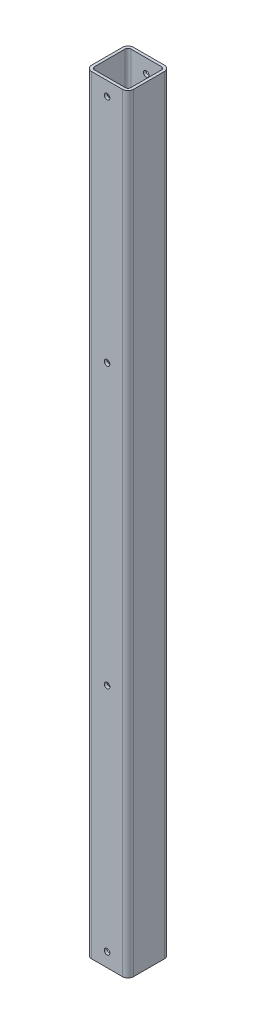
SolidWorks part; units mm, degrees
material "AISI 1010 钢，热轧条材"
ref_plane "前视基准面" through (0, 0, 0) normal (0, 0, 1) x (1, 0, 0)
ref_plane "上视基准面" through (0, 0, 0) normal (0, 1, 0) x (1, 0, 0)
ref_plane "右视基准面" through (0, 0, 0) normal (1, 0, 0) x (0, 0, -1)
sketch "草图1" plane through (0, 0, 0) normal (0, 1, 0) x (1, 0, 0)
  line L0 (-11, -13) -> (11, -13)
  line L1 (-11, -15) -> (11, -15)
  line L2 (-15, -11) -> (-15, 11)
  line L3 (-11, 15) -> (11, 15)
  line L4 (15, -11) -> (15, 11)
  line L5 (13, -11) -> (13, 11)
  line L6 (-11, 13) -> (11, 13)
  line L7 (-13, -11) -> (-13, 11)
  arc A0 (-11, -15) -> (-15, -11) centre (-11, -11) cw
  arc A1 (11, -15) -> (15, -11) centre (11, -11) ccw
  arc A2 (11, 15) -> (15, 11) centre (11, 11) cw
  arc A3 (-15, 11) -> (-11, 15) centre (-11, 11) cw
  arc A4 (11, -13) -> (13, -11) centre (11, -11) ccw
  arc A5 (11, 13) -> (13, 11) centre (11, 11) cw
  arc A6 (-13, 11) -> (-11, 13) centre (-11, 11) cw
  arc A7 (-11, -13) -> (-13, -11) centre (-11, -11) cw
extrude "凸台-拉伸1" add sketch "草图1" along normal mid plane 550
sketch "草图2" plane through (0, 0, 0) normal (0, 0, 1) x (1, 0, 0)
  line L0 (14.3201, 0) -> (-15, 0) construction
  line L1 (-15, 275) -> (-15, -275) construction
  line L2 (-11, 275) -> (11, 275) construction
  circle A0 centre (0, 265) radius 2
  circle A1 centre (0, 100) radius 2
  circle A2 centre (0, -100) radius 2
  circle A3 centre (0, -265) radius 2
  dimension "D1" = 4
  dimension "D2" = 10
  dimension "D3" = 100
  dimension "D4" = 15
extrude "切除-拉伸1" cut sketch "草图2" against normal through all both and the other way through all
